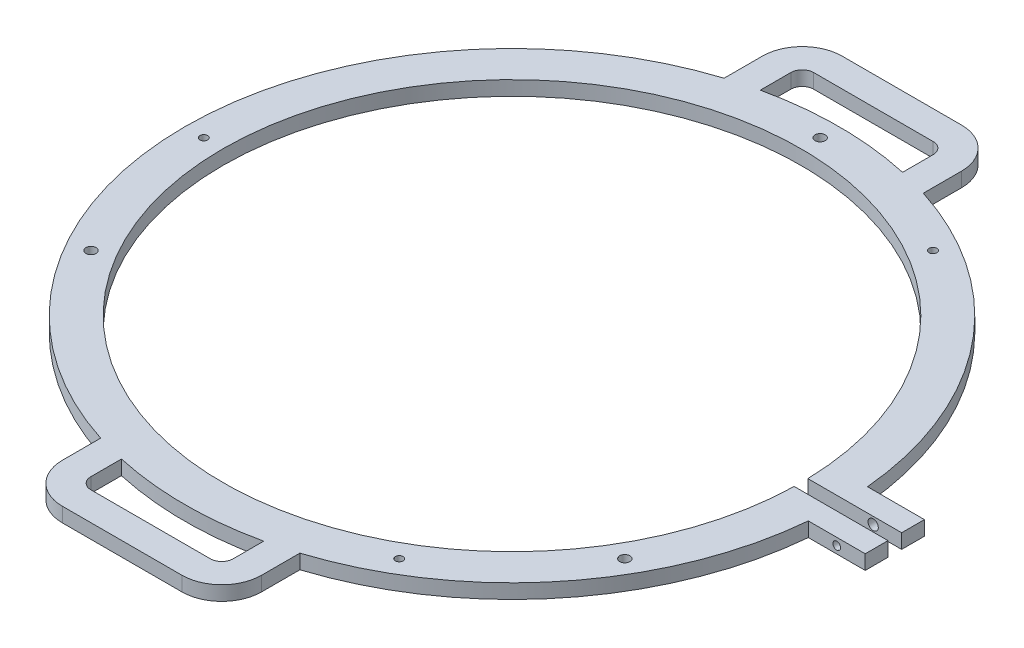
SolidWorks part; units mm, degrees
material "6061-T6 (SS)"
ref_plane "Front Plane" through (0, 0, 0) normal (0, 0, 1) x (1, 0, 0)
ref_plane "Top Plane" through (0, 0, 0) normal (0, 1, 0) x (1, 0, 0)
ref_plane "Right Plane" through (0, 0, 0) normal (1, 0, 0) x (0, 0, -1)
sketch "Sketch1" plane through (0, 0, 0) normal (0, 1, 0) x (1, 0, 0)
  line L0 (0, 0) -> (287.5, 0) construction
  line L1 (275.1443, 6) -> (253.9291, 6)
  line L2 (275.1443, 6) -> (336.3219, 6)
  line L4 (286.3219, 26) -> (336.3219, 26)
  line L5 (336.3219, 6) -> (336.3219, 26)
  line L6 (275.0672, -6) -> (336.3219, -6)
  line L8 (286.3219, -26) -> (336.3219, -26)
  line L9 (336.3219, -6) -> (336.3219, -26)
  line L10 (275.0672, -6) -> (253.9291, -6)
  arc A0 (253.9291, 6) -> (253.9291, -6) centre (0, 0) ccw
  arc A1 (286.3219, 26) -> (286.3219, -26) centre (0, 0) ccw
  dimension "D1" = 575
  dimension "D2" = 508
  dimension "D3" = 6
  dimension "D4" = 20
  dimension "D5" = 6
  dimension "D6" = 20
  dimension "D7" = 50
  dimension "D8" = 50
extrude "Boss-Extrude1" add sketch "Sketch1" along normal blind 12.7
hole_wizard "M8x1.25 Tapped Hole1 - For Lowering" positions "Sketch2" profile "Sketch3" tap size "M8x1.25" standard "ANSI Metric" end condition up to next
sketch "Sketch2" plane through (0, 12.7, 0) normal (0, 1, 0) x (1, 0, 0)
  line L6 (-287.5, 0) -> (-254, 0) construction
  line L8 (-254, 0) -> (0, 0) construction
  line L9 (127, -219.9705) -> (0, 0) construction
  line L11 (127, -219.9705) -> (143.75, -248.9823) construction
  arc A4 (286.3219, 26) -> (286.3219, -26) centre (0, 0) ccw construction
  circle A5 centre (0, 0) radius 254 construction
  arc A6 (253.9291, 6) -> (253.9291, -6) centre (0, 0) ccw construction
  point P20 (-270.75, 0)
  point P36 (135.375, 234.4764)
  point P37 (135.375, -234.4764)
  point P72 (-270.75, 0)
  point P86 (135.375, -234.4764)
  dimension "D1" = 3
  dimension "D2" = 120
sketch "Sketch3" plane through (135.375, 12.7, 234.4764) normal (1, 0, 0) x (0, 0, 1)
  line L0 (0, 0) -> (0, 12.7)
  line L1 (0, 12.7) -> (3.4, 12.7)
  line L2 (3.4, 12.7) -> (3.4, 0)
  line L5 (3.4, 0) -> (0, 0)
  line L11 (0, -6.35) -> (0, 107.95) construction
  dimension "Thru Tap Drill Dia." = 6.8
  dimension "Thru Tap Drill Depth" = 12.7
cosmetic thread "Hole Thread2" parameters "D2"=8
cosmetic thread "Hole Thread4" parameters "D2"=8
cosmetic thread "Hole Thread5" parameters "D2"=8
hole_wizard "M8 Clearance Hole1 - For Spacer Block" positions "Sketch5" profile "Sketch6" hole size "M8" standard "ANSI Metric" end condition up to next
sketch "Sketch5" plane through (0, 12.7, 0) normal (0, 1, 0) x (1, 0, 0)
  line L0 (0, 287.5) -> (0, 254) construction
  line L2 (0, 254) -> (0, 0) construction
  line L3 (0, 0) -> (-219.9705, -127) construction
  line L4 (-219.9705, -127) -> (-248.9823, -143.75) construction
  line L6 (0, 0) -> (219.9705, -127) construction
  line L7 (219.9705, -127) -> (248.9823, -143.75) construction
  arc A0 (286.3219, 26) -> (286.3219, -26) centre (0, 0) ccw construction
  circle A1 centre (0, 0) radius 254 construction
  arc A2 (91.0592, -237.1165) -> (79.7583, -241.1527) centre (0, 0) ccw construction
  arc A3 (120.7892, -260.895) -> (71.8188, -278.3852) centre (0, 0) ccw construction
  point P0 (0, 270.75)
  point P16 (0, 270.75)
  point P21 (234.4764, -135.375)
  point P22 (-234.4764, -135.375)
  point P36 (-234.4764, -135.375)
  point P44 (234.4764, -135.375)
  dimension "D1" = 3
sketch "Sketch6" plane through (0, 12.7, -270.75) normal (1, 0, 0) x (0, 0, 1)
  line L0 (0, 0) -> (0, 12.7)
  line L1 (0, 12.7) -> (4.5, 12.7)
  line L2 (4.5, 12.7) -> (4.5, 0)
  line L5 (4.5, 0) -> (0, 0)
  line L11 (0, -6.35) -> (0, 107.95) construction
  dimension "Thru Hole Dia." = 9
  dimension "Thru Hole Depth" = 12.7
hole_wizard "M8 Clearance Hole2 - For Clamp Tightening" positions "Sketch9" profile "Sketch8" hole size "M8" standard "ANSI Metric"
sketch "Sketch9" plane through (0, 0, -26) normal (0, 0, -1) x (-1, 0, 0)
  line L0 (-311.3219, 12.7) -> (-311.3219, 0) construction
  line L1 (-336.3219, 12.7) -> (-286.3219, 12.7) construction
  line L2 (-336.3219, 0) -> (-286.3219, 0) construction
  point P0 (-311.3219, 6.35)
  point P11 (-311.3219, 6.35)
sketch "Sketch8" plane through (311.3219, 6.35, -26) normal (1, 0, 0) x (0, 1, 0)
  line L0 (0, 0) -> (0, 20)
  line L1 (0, 20) -> (4.5, 20)
  line L2 (4.5, 20) -> (4.5, 0)
  line L5 (4.5, 0) -> (0, 0)
  line L11 (0, -6.35) -> (0, 107.95) construction
  dimension "Thru Hole Dia." = 9
  dimension "Thru Hole Depth" = 20
hole_wizard "M8x1.25 Tapped Hole2 - For Clamp Tightening" positions "Sketch10" profile "Sketch11" tap size "M8x1.25" standard "ANSI Metric" end condition up to next
sketch "Sketch10" plane through (0, 0, 26) normal (0, 0, 1) x (1, 0, 0)
  point P0 (311.3219, 6.35)
sketch "Sketch11" plane through (311.3219, 6.35, 26) normal (1, 0, 0) x (0, -1, 0)
  line L0 (0, 0) -> (0, 20)
  line L1 (0, 20) -> (3.4, 20)
  line L2 (3.4, 20) -> (3.4, 0)
  line L5 (3.4, 0) -> (0, 0)
  line L11 (0, -6.35) -> (0, 107.95) construction
  dimension "Thru Tap Drill Dia." = 6.8
  dimension "Thru Tap Drill Depth" = 20
cosmetic thread "Hole Thread7" parameters "D2"=8
hole_wizard "5/16 (0.3125) Diameter Hole1 - For Handles" positions "Sketch12" profile "Sketch13" hole size "5/16" standard "ANSI Inch"
sketch "Sketch12" plane through (0, 0, 0) normal (0, -1, 0) x (-1, 0, 0)
  circle A2 centre (0, 0) radius 275 construction
  point P49 (-267.5682, 63.5)
  point P51 (-267.5682, -63.5)
  point P53 (267.5682, 63.5)
  point P55 (267.5682, -63.5)
  dimension "D1" = 550
  dimension "D2" = 127
sketch "Sketch13" plane through (-267.5682, 0, 63.5) normal (1, 0, 0) x (0, 0, -1)
  line L0 (0, 0) -> (0, 12.7)
  line L1 (0, 12.7) -> (3.9687, 12.7)
  line L2 (3.9687, 12.7) -> (3.9687, 0)
  line L5 (3.9687, 0) -> (0, 0)
  line L11 (0, -6.35) -> (0, 107.95) construction
  dimension "Thru Hole Dia." = 7.9375
  dimension "Thru Hole Depth" = 12.7
sketch "Sketch14" plane through (0, 12.7, 0) normal (0, 1, 0) x (1, 0, 0)
  line L0 (0, 0) -> (0, 287.5) construction
  line L1 (-52.5, 342.5) -> (52.5, 342.5)
  line L2 (-87.5, 307.5) -> (-87.5, 273.8613)
  line L4 (87.5, 307.5) -> (87.5, 273.8613)
  line L5 (-62.5, 307.5) -> (-62.5, 280.6243)
  line L6 (-52.5, 317.5) -> (52.5, 317.5)
  line L7 (62.5, 307.5) -> (62.5, 280.6243)
  line L8 (-62.5, 307.5) -> (-62.5, 273.8613) construction
  line L9 (62.5, 307.5) -> (62.5, 273.8613) construction
  line L10 (0, 287.5) -> (0, 342.5) construction
  arc A0 (286.3219, 26) -> (286.3219, -26) centre (0, 0) ccw construction
  arc A1 (87.5, 273.8613) -> (62.5, 280.6243) centre (0, 0) ccw
  arc A2 (52.5, 342.5) -> (87.5, 307.5) centre (52.5, 307.5) cw
  arc A3 (-52.5, 342.5) -> (-87.5, 307.5) centre (-52.5, 307.5) ccw
  arc A4 (-52.5, 317.5) -> (-62.5, 307.5) centre (-52.5, 307.5) ccw
  arc A5 (52.5, 317.5) -> (62.5, 307.5) centre (52.5, 307.5) cw
  arc A6 (-62.5, 280.6243) -> (-87.5, 273.8613) centre (0, 0) ccw
  point P23 (24.9147, 303.3226)
  point P26 (0, 287.5)
  dimension "D1" = 35
  dimension "D2" = 25
  dimension "D3" = 55
  dimension "D4" = 175
extrude "Boss-Extrude2 - Handles" add sketch "Sketch14" against normal up to surface (12.7 mm away) up to face at (0, 0, -266.25)
mirror "Mirror1" about plane through (0, 0, 0) normal (0, 0, 1) of "Boss-Extrude2 - Handles"
